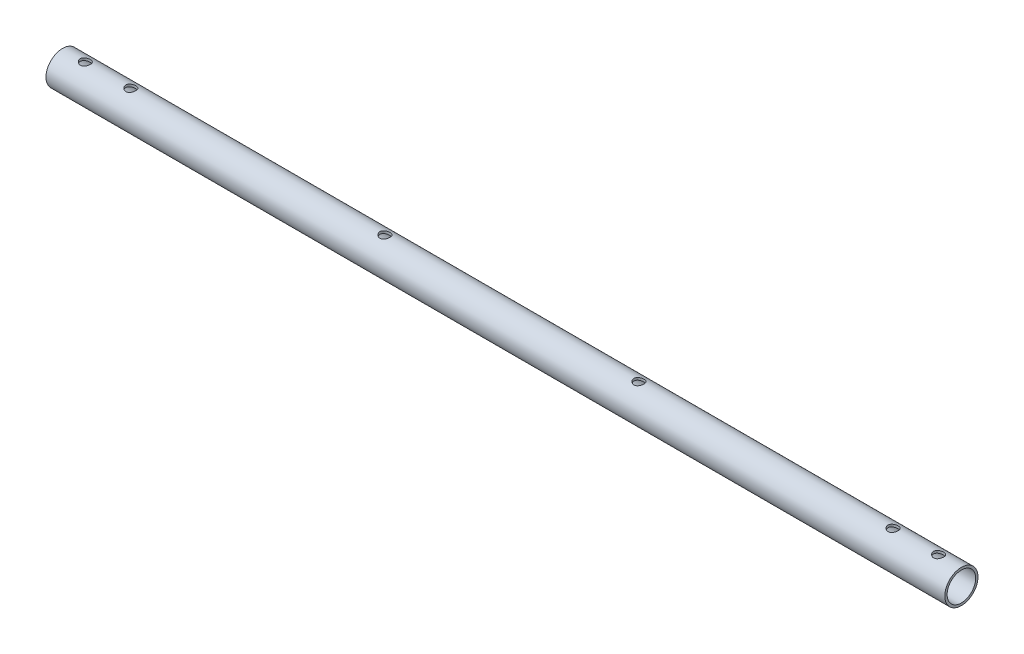
SolidWorks part; units mm, degrees
material "ASTM A36 Steel"
ref_plane "Front Plane" through (0, 0, 0) normal (0, 0, 1) x (1, 0, 0)
ref_plane "Top Plane" through (0, 0, 0) normal (0, 1, 0) x (1, 0, 0)
ref_plane "Right Plane" through (0, 0, 0) normal (1, 0, 0) x (0, 0, -1)
sketch "Sketch1" plane through (0, 0, 0) normal (1, 0, 0) x (0, 0, -1)
  circle A0 centre (0, 0) radius 36.5
  circle A1 centre (0, 0) radius 31.34
  dimension "D1" = 73
  dimension "D2" = 5.16
extrude "Boss-Extrude1" add sketch "Sketch1" along normal blind 1975
sketch "Sketch2" plane through (0, 0, 0) normal (0, 1, 0) x (1, 0, 0)
  line L0 (0, 36.5) -> (0, -36.5) construction
  circle A0 centre (50, 0) radius 11
  dimension "D1" = 22
  dimension "D2" = 50
extrude "Cut-Extrude2" cut sketch "Sketch2" against normal through all both and the other way through all
sketch "Sketch3" plane through (0, 0, 0) normal (0, 1, 0) x (1, 0, 0)
  circle A0 centre (150, 0) radius 11
  circle A1 centre (50, 0) radius 11 construction
  dimension "D1" = 22
  dimension "D2" = 100
extrude "Cut-Extrude3" cut sketch "Sketch3" against normal through all both and the other way through all
pattern_linear "LPattern1" count 4 spacing 558.3333 along (1, 0, 0) of "Cut-Extrude3"
sketch "Sketch4" plane through (0, 0, 0) normal (0, 1, 0) x (1, 0, 0)
  circle A0 centre (1924.9999, 0) radius 11
  circle A1 centre (1824.9999, 0) radius 11 construction
  dimension "D1" = 22
  dimension "D2" = 100
extrude "Cut-Extrude4" cut sketch "Sketch4" against normal through all both and the other way through all
